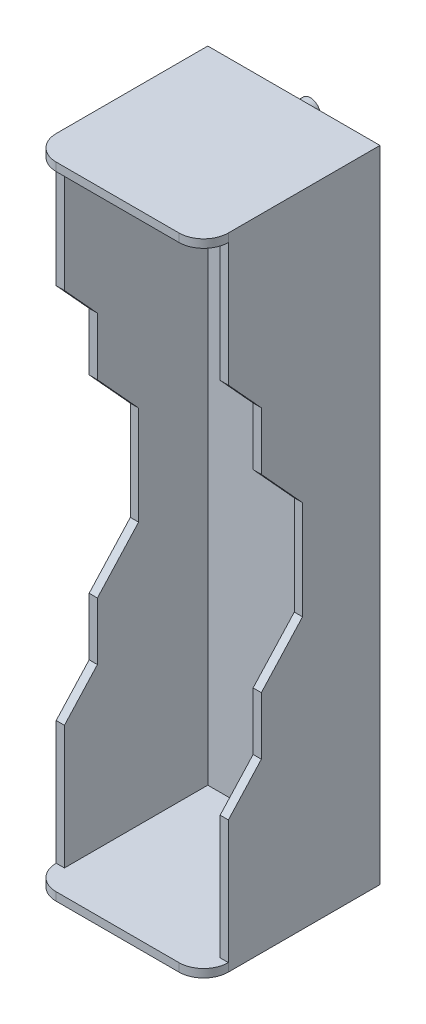
SolidWorks part; units mm, degrees
ref_plane "Front Plane" through (0, 0, 0) normal (0, 0, 1) x (1, 0, 0)
ref_plane "Top Plane" through (0, 0, 0) normal (0, 1, 0) x (1, 0, 0)
ref_plane "Right Plane" through (0, 0, 0) normal (1, 0, 0) x (0, 0, -1)
sketch "Sketch1" plane through (0, 0, 0) normal (0, 1, 0) x (1, 0, 0)
  line L1 (-10.45, 21.4) -> (10.45, 21.4)
  line L2 (-10.45, 21.4) -> (-10.45, 0)
  line L3 (-10.45, 0) -> (10.45, 0)
  line L4 (10.45, 21.4) -> (10.45, 0)
  dimension "D1" = 20.9
  dimension "D2" = 21.4
extrude "Boss-Extrude1" add sketch "Sketch1" along normal mid plane 77.7
sketch "Sketch2" plane through (0, 0, 0) normal (0, 0, -1) x (-1, 0, 0)
  line L0 (10.45, 38.85) -> (10.45, -38.85) construction
  line L1 (9.45, 37.85) -> (-9.45, 37.85)
  line L2 (9.45, 37.85) -> (9.45, -37.85)
  line L3 (9.45, -37.85) -> (-9.45, -37.85)
  line L4 (-9.45, 37.85) -> (-9.45, -37.85)
  line L5 (-10.45, 38.85) -> (10.45, 38.85) construction
  line L6 (-10.45, 38.85) -> (-10.45, -38.85) construction
  line L7 (-10.45, -38.85) -> (10.45, -38.85) construction
  dimension "D1" = 1
  dimension "D2" = 1
  dimension "D3" = 1
  dimension "D4" = 1
extrude "Cut-Extrude1" cut sketch "Sketch2" along normal offset from surface (20.4 mm away) 1 up to face at (0, 0, -21.4)
sketch "Sketch3" plane through (10.45, 0, 0) normal (1, 0, 0) x (0, 0, -1)
  line L0 (0, 37.85) -> (3, 37.85)
  line L1 (0, 38.85) -> (0, -38.85) construction
  line L2 (3, 37.85) -> (3, 22.85)
  line L3 (3, 22.85) -> (7, 18.4722)
  line L4 (7, 18.4722) -> (7, 11.4722)
  line L5 (7, 11.4722) -> (12, 6)
  line L6 (12, 6) -> (12, -6)
  line L7 (0, 0) -> (21.4, 0) construction
  line L8 (21.4, 38.85) -> (21.4, -38.85) construction
  line L9 (0, 37.85) -> (0, -37.85)
  line L10 (7, -11.4722) -> (12, -6)
  line L11 (0, 38.85) -> (21.4, 38.85) construction
  line L12 (7, -18.4722) -> (7, -11.4722)
  line L13 (3, -22.85) -> (7, -18.4722)
  line L14 (3, -37.85) -> (3, -22.85)
  line L15 (0, -37.85) -> (3, -37.85)
  point P16 (12, 0)
  dimension "D1" = 1
  dimension "D2" = 3
  dimension "D3" = 12
  dimension "D4" = 6
  dimension "D5" = 15
  dimension "D6" = 7
  dimension "D7" = 7
extrude "Cut-Extrude4" cut sketch "Sketch3" against normal through all
sketch "Sketch4" plane through (0, 0, -21.4) normal (0, 0, -1) x (-1, 0, 0)
  line L0 (0, 0) -> (0, 38.85) construction
  line L1 (-10.45, 38.85) -> (10.45, 38.85) construction
  line L2 (-10.45, 0) -> (10.45, 0) construction
  line L3 (-10.45, 38.85) -> (-10.45, -38.85) construction
  line L4 (10.45, 38.85) -> (10.45, -38.85) construction
  circle A0 centre (0, -36.45) radius 1.2
  circle A1 centre (0, 36.45) radius 1.2
  dimension "D2" = 2.4
  dimension "D1" = 72.9
extrude "Boss-Extrude2" add sketch "Sketch4" along normal blind 2
sketch "Sketch5" plane through (0, 0, -21.4) normal (0, 0, -1) x (-1, 0, 0)
  line L0 (0, 0) -> (0, 38.85) construction
  line L1 (-10.45, 38.85) -> (10.45, 38.85) construction
  line L2 (10.45, 0) -> (-10.45, 0) construction
  line L3 (10.45, 38.85) -> (10.45, -38.85) construction
  line L4 (-10.45, 38.85) -> (-10.45, -38.85) construction
  circle A0 centre (0, -27.805) radius 1.6
  circle A1 centre (0, 27.805) radius 1.6
  dimension "D1" = 3.2
  dimension "D2" = 55.61
extrude "Cut-Extrude5" cut sketch "Sketch5" against normal through all
fillet "Fillet1" radius 3 4 edges at (-10.45, 38.35, 0) (10.45, 38.35, 0) (-10.45, -38.35, 0) (10.45, -38.35, 0)
